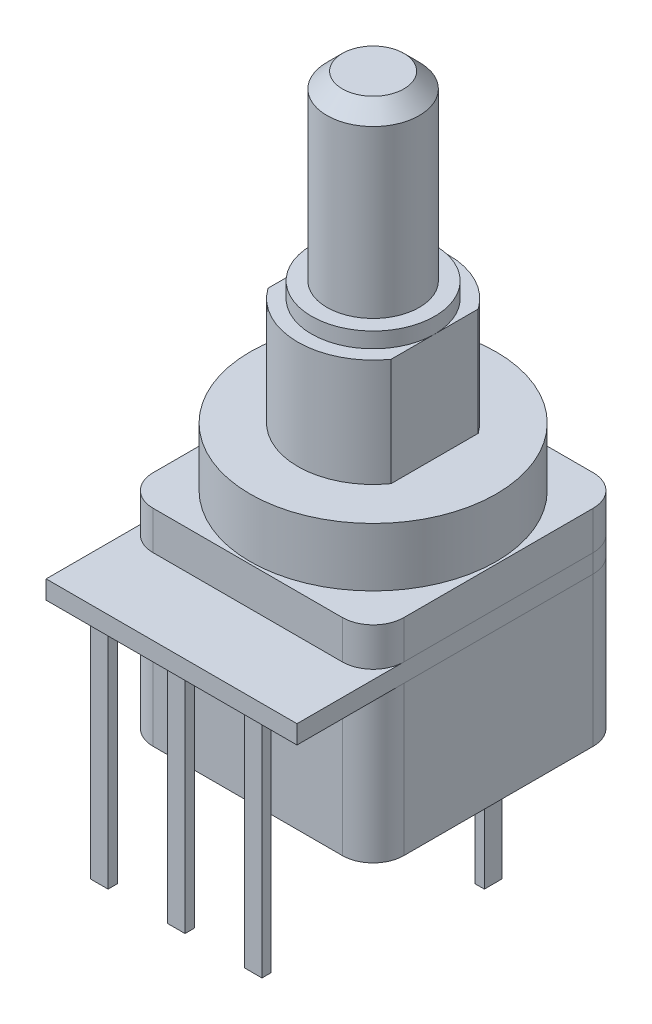
SolidWorks part; units mm, degrees
ref_plane "Alzado" through (0, 0, 0) normal (0, 0, 1) x (1, 0, 0)
ref_plane "Planta" through (0, 0, 0) normal (0, 1, 0) x (1, 0, 0)
ref_plane "Vista lateral" through (0, 0, 0) normal (1, 0, 0) x (0, 0, -1)
sketch "Croquis1" plane through (0, 0, 0) normal (0, 1, 0) x (1, 0, 0)
  line L1 (-8.15, -8.15) -> (8.15, -8.15)
  line L2 (-8.15, -8.15) -> (-8.15, 8.15)
  line L3 (-8.15, 8.15) -> (8.15, 8.15)
  line L4 (8.15, -8.15) -> (8.15, 8.15)
  line L5 (-8.15, -8.15) -> (8.15, 8.15) construction
  line L6 (-8.15, 8.15) -> (8.15, -8.15) construction
  point P0 (0, 0)
  dimension "D1" = 16.3
extrude "Saliente-Extruir1" add sketch "Croquis1" against normal blind 9.7
fillet "Redondeo1" radius 2 4 edges at (8.15, -4.85, 8.15) (-8.15, -4.85, 8.15) (8.15, -4.85, -8.15) (-8.15, -4.85, -8.15)
sketch "Croquis2" plane through (0, 0, 0) normal (0, 1, 0) x (1, 0, 0)
  line L0 (-8.15, -13.1) -> (8.15, -13.1)
  line L4 (-6.15, -8.15) -> (6.15, -8.15)
  line L5 (8.15, -6.15) -> (8.15, 6.15)
  line L6 (6.15, 8.15) -> (-6.15, 8.15)
  line L7 (-8.15, 6.15) -> (-8.15, -6.15)
  line L9 (8.15, -13.1) -> (8.15, 6.15)
  line L10 (6.15, 8.15) -> (-6.15, 8.15)
  line L11 (-8.15, 6.15) -> (-8.15, -13.1)
  arc A4 (6.15, -8.15) -> (8.15, -6.15) centre (6.15, -6.15) ccw
  arc A5 (8.15, 6.15) -> (6.15, 8.15) centre (6.15, 6.15) ccw
  arc A6 (-6.15, 8.15) -> (-8.15, 6.15) centre (-6.15, 6.15) ccw
  arc A7 (-8.15, -6.15) -> (-6.15, -8.15) centre (-6.15, -6.15) ccw
  arc A9 (8.15, 6.15) -> (6.15, 8.15) centre (6.15, 6.15) ccw
  arc A10 (-6.15, 8.15) -> (-8.15, 6.15) centre (-6.15, 6.15) ccw
  dimension "D2" = 21.25
  dimension "D1" = 0
extrude "Saliente-Extruir2" add sketch "Croquis2" along normal blind 1.2 separate body
sketch "Croquis3" plane through (0, 1.2, 0) normal (0, 1, 0) x (1, 0, 0)
  line L4 (8.15, -6.15) -> (8.15, 6.15)
  line L5 (-6.15, -8.15) -> (6.15, -8.15)
  line L6 (-8.15, 6.15) -> (-8.15, -6.15)
  line L7 (6.15, 8.15) -> (-6.15, 8.15)
  line L8 (8.15, -6.15) -> (8.15, 6.15)
  line L9 (-6.15, -8.15) -> (6.15, -8.15)
  line L10 (-8.15, 6.15) -> (-8.15, -6.15)
  line L11 (6.15, 8.15) -> (-6.15, 8.15)
  arc A4 (6.15, -8.15) -> (8.15, -6.15) centre (6.15, -6.15) ccw
  arc A5 (-8.15, -6.15) -> (-6.15, -8.15) centre (-6.15, -6.15) ccw
  arc A6 (-6.15, 8.15) -> (-8.15, 6.15) centre (-6.15, 6.15) ccw
  arc A7 (8.15, 6.15) -> (6.15, 8.15) centre (6.15, 6.15) ccw
  arc A8 (6.15, -8.15) -> (8.15, -6.15) centre (6.15, -6.15) ccw
  arc A9 (-8.15, -6.15) -> (-6.15, -8.15) centre (-6.15, -6.15) ccw
  arc A10 (-6.15, 8.15) -> (-8.15, 6.15) centre (-6.15, 6.15) ccw
  arc A11 (8.15, 6.15) -> (6.15, 8.15) centre (6.15, 6.15) ccw
  dimension "D1" = 0
extrude "Saliente-Extruir3" add sketch "Croquis3" along normal blind 2.5 separate body
sketch "Croquis4" plane through (0, 3.7, 0) normal (0, 1, 0) x (1, 0, 0)
  circle A0 centre (0, 0) radius 8
  dimension "D1" = 16
extrude "Saliente-Extruir4" add sketch "Croquis4" along normal blind 3.8
sketch "Croquis6" plane through (0, 7.5, 0) normal (0, 1, 0) x (1, 0, 0)
  line L0 (-4, 2.8302) -> (-4, -2.8302)
  line L1 (0, 0) -> (0, 9.5964) construction
  line L2 (4, 2.8302) -> (4, -2.8302)
  arc A0 (4, 2.8302) -> (-4, 2.8302) centre (0, 0) ccw
  arc A1 (-4, -2.8302) -> (4, -2.8302) centre (0, 0) ccw
  dimension "D2" = 4.9
  dimension "D1" = 8
extrude "Saliente-Extruir5" add sketch "Croquis6" along normal blind 7
sketch "Croquis7" plane through (0, 14.5, 0) normal (0, 1, 0) x (1, 0, 0)
  circle A0 centre (0, 0) radius 4
  dimension "D1" = 8
extrude "Saliente-Extruir6" add sketch "Croquis7" along normal blind 1
sketch "Croquis8" plane through (0, 15.5, 0) normal (0, 1, 0) x (1, 0, 0)
  circle A0 centre (0, 0) radius 3
  dimension "D1" = 6
extrude "Saliente-Extruir7" add sketch "Croquis8" along normal blind 11.8 and the other way blind 1 separate body
chamfer "Chaflán1" distance 1 angle 45 1 edges at (0, 27.3, 3)
sketch "Croquis9" plane through (0, -9.7, 0) normal (0, -1, 0) x (1, 0, 0)
  line L1 (-0.575, -7.2) -> (0.575, -7.2)
  line L2 (-0.575, -7.2) -> (-0.575, -7.8)
  line L3 (-0.575, -7.8) -> (0.575, -7.8)
  line L4 (0.575, -7.2) -> (0.575, -7.8)
  line L6 (7.2, 0.575) -> (7.8, 0.575)
  line L7 (7.2, 0.575) -> (7.2, -0.575)
  line L8 (7.2, -0.575) -> (7.8, -0.575)
  line L9 (7.8, 0.575) -> (7.8, -0.575)
  line L10 (0, 0) -> (0, 15.1145) construction
  line L11 (0, 0) -> (0, -7.2) construction
  line L12 (0, 0) -> (7.2, 0) construction
  line L13 (-7.8, 0.575) -> (-7.8, -0.575)
  line L14 (-7.2, -0.575) -> (-7.8, -0.575)
  line L15 (-7.2, 0.575) -> (-7.2, -0.575)
  line L16 (-7.2, 0.575) -> (-7.8, 0.575)
  point P4 (-7.8, 0)
  point P5 (-0.575, -7.5)
  point P10 (-7.5, 0.575)
  point P11 (7.5, 0.575)
  dimension "D1" = 0.6
  dimension "D2" = 1.15
  dimension "D3" = 15
  dimension "D4" = 7.5
extrude "Saliente-Extruir8" add sketch "Croquis9" along normal blind 4.85 separate body
sketch "Croquis10" plane through (0, 1.2, 0) normal (0, 1, 0) x (1, 0, 0)
  line L0 (0, 0) -> (0, -12.2) construction
  line L1 (-5.575, -12.8) -> (-4.425, -12.8)
  line L2 (-5.575, -12.8) -> (-5.575, -12.2)
  line L3 (-5.575, -12.2) -> (-4.425, -12.2)
  line L4 (-4.425, -12.8) -> (-4.425, -12.2)
  line L5 (4.425, -12.8) -> (4.425, -12.2)
  line L6 (5.575, -12.2) -> (4.425, -12.2)
  line L7 (5.575, -12.8) -> (5.575, -12.2)
  line L8 (5.575, -12.8) -> (4.425, -12.8)
  line L9 (-7.2, 0.575) -> (-7.2, -0.575) construction
  line L10 (-7.2, -0.575) -> (-7.8, -0.575) construction
  line L11 (-4.425, -12.5) -> (4.425, -12.5) construction
  line L12 (-0.575, -12.8) -> (0.575, -12.8)
  line L13 (-0.575, -12.8) -> (-0.575, -12.2)
  line L14 (-0.575, -12.2) -> (0.575, -12.2)
  line L15 (0.575, -12.8) -> (0.575, -12.2)
  point P4 (-4.425, -12.5)
  point P6 (-5, -12.8)
  point P23 (0, -12.2)
  dimension "D1" = 12.5
  dimension "D2" = 5
extrude "Saliente-Extruir9" add sketch "Croquis10" against normal up to surface (15.75 mm away) separate body up to face at (-7.5, -14.55, 0)
